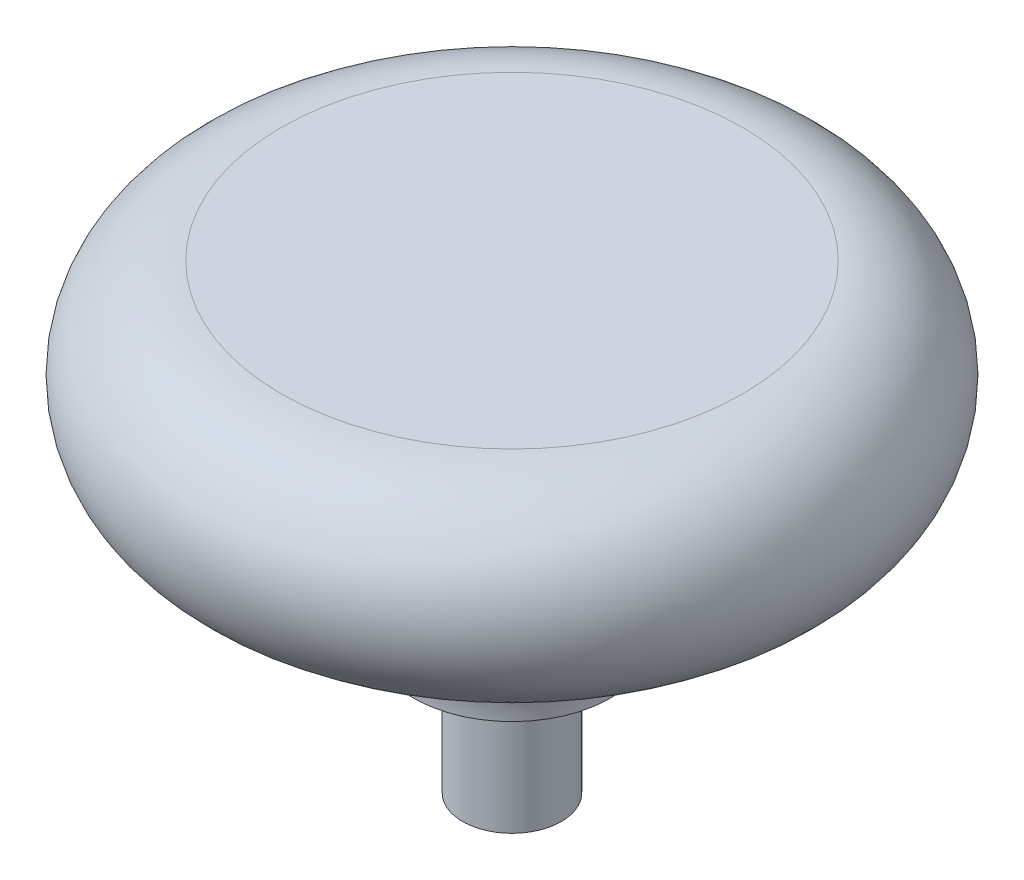
SolidWorks part; units mm, degrees
ref_plane "Front Plane" through (0, 0, 0) normal (0, 0, 1) x (1, 0, 0)
ref_plane "Top Plane" through (0, 0, 0) normal (0, 1, 0) x (1, 0, 0)
ref_plane "Right Plane" through (0, 0, 0) normal (1, 0, 0) x (0, 0, -1)
sketch "Sketch1" plane through (0, 0, 0) normal (0, 0, 1) x (1, 0, 0)
  line L0 (0, 0) -> (0, 13227.9158) construction
  line L1 (0, 0) -> (13227.9158, 0) construction
  line L2 (2.38, 0) -> (2.38, 6.35)
  line L3 (2.38, 6.35) -> (4.765, 6.35)
  line L4 (11.12, 22.22) -> (0, 22.22)
  line L5 (2.38, 0) -> (0, 0)
  line L6 (0, 22.22) -> (0, 0)
  arc A0 (4.765, 6.35) -> (11.1179, 12.7) centre (11.115, 6.35) cw
  arc A1 (11.1179, 12.7) -> (11.12, 22.22) centre (11.12, 17.46) ccw
  dimension "D1" = 4.76
  dimension "D2" = 11.12
  dimension "D4" = 6.35
  dimension "D3" = 2.38
  dimension "D5" = 2.385
  dimension "D6" = 6.35
revolve "Revolve1" add sketch "Sketch1" angle 360 about L0
